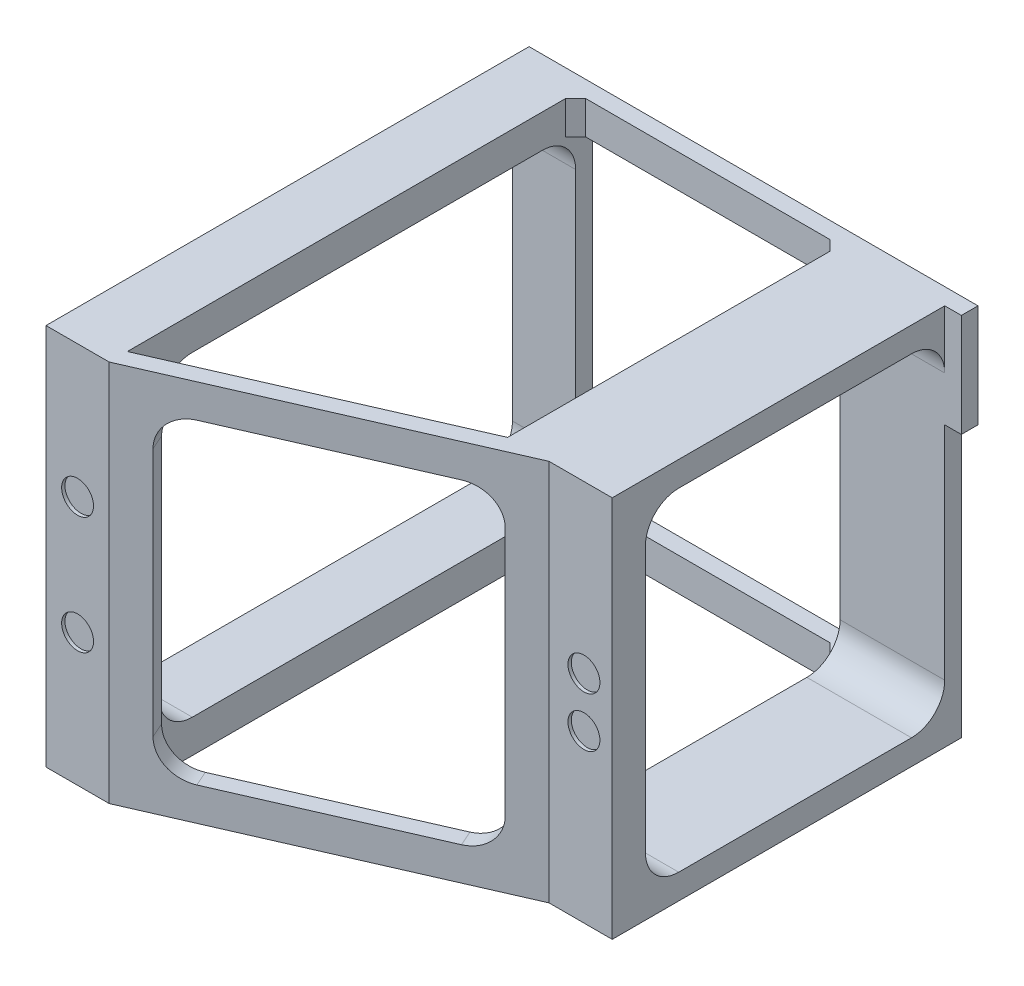
SolidWorks part; units mm, degrees
ref_plane "Front Plane" through (0, 0, 0) normal (1, 0, 0) x (0, 1, 0)
ref_plane "Top Plane" through (0, 0, 0) normal (0, 0, 1) x (0, 1, 0)
ref_plane "Right Plane" through (0, 0, 0) normal (0, 1, 0) x (-1, 0, 0)
sketch "Sketch2" plane through (0, 0, 0) normal (0, 0, 1) x (0, 1, 0)
  line L0 (0, 100.3268) -> (0, -104.3828) construction
  line L1 (0, 0) -> (145.436, 0) construction
  line L2 (-57.5, -65) -> (57.5, -65)
  line L3 (-57.5, -65) -> (-57.5, 65)
  line L4 (-57.5, 65) -> (57.5, 65)
  line L5 (57.5, -65) -> (57.5, 65)
  circle A0 centre (-18.09, -55.5) radius 4.8
  circle A1 centre (18.08, -55.5) radius 4.8
  dimension "D3" = 9.6
  dimension "D4" = 9.6
  dimension "D5" = 39.42
  dimension "D1" = 115
  dimension "D2" = 130
  dimension "D6" = 9.5
  dimension "D7" = 36.17
extrude "Boss-Extrude1" add sketch "Sketch2" along normal blind 5
sketch "Sketch3" plane through (0, 57.5, 0) normal (0, 1, 0) x (-1, 0, 0)
  line L0 (-65, 5) -> (-46, 5)
  line L1 (-65, 5) -> (65, 5) construction
  line L2 (-46, 5) -> (46, 45.27)
  line L3 (46, 45.27) -> (65, 45.27)
  line L4 (65, 45.27) -> (65, 39.812)
  line L6 (46, 39.812) -> (-33.5307, 5)
  line L7 (65, 5) -> (65, 0) construction
  line L8 (46, 39.812) -> (65, 39.812)
  line L9 (-65, 5) -> (-65, 0)
  line L10 (-65, 5) -> (-65, 0) construction
  line L11 (-65, 0) -> (-33.5307, 0)
  line L12 (-65, 0) -> (65, 0) construction
  line L13 (-33.5307, 0) -> (-33.5307, 5)
  point P5 (-33.5307, 0)
  dimension "D1" = 19
  dimension "D2" = 19
  dimension "D3" = 40.27
  dimension "D4" = 5
extrude "Boss-Extrude2" add sketch "Sketch3" against normal up to surface (115 mm away) up to face at (0, -57.5, 2.5)
sketch "Sketch4" plane through (0, 0, 5) normal (0, 0, 1) x (1, 0, 0)
  line L0 (33.5307, -57.5) -> (33.5307, 57.5)
  line L1 (-46, 57.5) -> (46, 57.5) construction
  line L2 (33.5307, 57.5) -> (-65, 57.5)
  line L3 (-65, 57.5) -> (-65, -57.5)
  line L4 (-65, -57.5) -> (33.5307, -57.5)
extrude "Cut-Extrude1" cut sketch "Sketch4" against normal blind 5
sketch "Sketch5" plane through (0, 0, 5) normal (0, 0, 1) x (1, 0, 0)
  line L0 (0, 0) -> (99.3947, 0) construction
  line L1 (65, -57.5) -> (65, 57.5) construction
  circle A0 centre (56.5, 7.5) radius 4.8
  circle A1 centre (56.5, -7.5) radius 4.8
  dimension "D2" = 9.6
  dimension "D3" = 9.6
  dimension "D1" = 15
  dimension "D4" = 7.5
  dimension "D5" = 8.5
extrude "Cut-Extrude2" cut sketch "Sketch5" against normal blind 1
sketch "Sketch6" plane through (0, 0, 45.27) normal (0, 0, 1) x (1, 0, 0)
  line L0 (0, 0) -> (90.3346, 0) construction
  line L1 (-65, -57.5) -> (-65, 57.5) construction
  circle A0 centre (-55.5, 17.65) radius 4.8
  circle A1 centre (-55.5, -17.65) radius 4.8
  dimension "D3" = 9.6
  dimension "D4" = 9.6
  dimension "D1" = 35.3
  dimension "D5" = 9.5
extrude "Cut-Extrude4" cut sketch "Sketch6" against normal blind 1
sketch "Sketch7" plane through (0, 0, 39.812) normal (0, 0, -1) x (1, 0, 0)
  line L1 (-65, -57.5) -> (-46, -57.5)
  line L2 (-65, -57.5) -> (-65, 57.5)
  line L3 (-65, 57.5) -> (-46, 57.5)
  line L4 (-46, -57.5) -> (-46, 57.5)
extrude "Boss-Extrude3" add sketch "Sketch7" along normal up to surface (39.812 mm away) up to face at (49.2654, 0, 0)
sketch "Sketch8" plane through (0, 0, 0) normal (0, 0, -1) x (1, 0, 0)
  line L1 (-65, 57.5) -> (-46, 57.5)
  line L2 (-65, 57.5) -> (-65, -57.5)
  line L3 (-65, -57.5) -> (-46, -57.5)
  line L4 (-46, 57.5) -> (-46, -57.5)
  line L5 (33.5307, 57.5) -> (65, 57.5)
  line L6 (33.5307, 57.5) -> (33.5307, -57.5)
  line L7 (33.5307, -57.5) -> (65, -57.5)
  line L8 (65, 57.5) -> (65, -57.5)
extrude "Boss-Extrude4" add sketch "Sketch8" along normal blind 100
sketch "Sketch9" plane through (-65, 0, 0) normal (-1, 0, 0) x (0, -1, 0)
  line L0 (57.5, 45.27) -> (-57.5, 45.27) construction
  line L1 (-37.5, -95) -> (37.5, -95)
  line L2 (-47.5, -85) -> (-47.5, 20.27)
  line L3 (-37.5, 30.27) -> (37.5, 30.27)
  line L4 (47.5, -85) -> (47.5, 20.27)
  line L5 (57.5, -100) -> (-57.5, -100) construction
  line L6 (-57.5, -100) -> (-57.5, 45.27) construction
  line L7 (57.5, 45.27) -> (57.5, -100) construction
  arc A0 (37.5, -95) -> (47.5, -85) centre (37.5, -85) ccw
  arc A1 (-37.5, -95) -> (-47.5, -85) centre (-37.5, -85) cw
  arc A2 (37.5, 30.27) -> (47.5, 20.27) centre (37.5, 20.27) cw
  arc A3 (-47.5, 20.27) -> (-37.5, 30.27) centre (-37.5, 20.27) cw
  dimension "D5" = 10
  dimension "D1" = 15
  dimension "D2" = 5
  dimension "D3" = 10
  dimension "D4" = 10
extrude "Cut-Extrude5" cut sketch "Sketch9" against normal up to surface (19 mm away) up to face at (-46, 0, -30.094)
sketch "Sketch10" plane through (65, 0, 0) normal (1, 0, 0) x (0, 1, 0)
  line L0 (-57.5, 5) -> (57.5, 5) construction
  line L1 (-40, -95) -> (40, -95)
  line L2 (-50, -85) -> (-50, -15)
  line L3 (-40, -5) -> (40, -5)
  line L4 (50, -85) -> (50, -15)
  line L5 (-57.5, 5) -> (-57.5, -100) construction
  line L6 (57.5, 5) -> (57.5, -100) construction
  line L7 (57.5, -100) -> (-57.5, -100) construction
  arc A0 (40, -95) -> (50, -85) centre (40, -85) ccw
  arc A1 (40, -5) -> (50, -15) centre (40, -15) cw
  arc A2 (-40, -95) -> (-50, -85) centre (-40, -85) cw
  arc A3 (-50, -15) -> (-40, -5) centre (-40, -15) cw
  dimension "D5" = 10
  dimension "D1" = 10
  dimension "D2" = 7.5
  dimension "D3" = 7.5
  dimension "D4" = 5
extrude "Cut-Extrude6" cut sketch "Sketch10" against normal up to surface (31.4693 mm away) up to face at (33.5307, 0, -47.5)
sketch "Sketch11" plane through (9.233, 0, 21.0935) normal (0.401, 0, 0.9161) x (0.9161, 0, -0.401)
  line L0 (-60.2925, 57.5) -> (40.1349, 57.5) construction
  line L1 (-40.2925, 47.5) -> (20.1349, 47.5)
  line L2 (-50.2925, 37.5) -> (-50.2925, -37.5)
  line L3 (-40.2925, -47.5) -> (20.1349, -47.5)
  line L4 (30.1349, 37.5) -> (30.1349, -37.5)
  line L5 (40.1349, -57.5) -> (-60.2925, -57.5) construction
  line L6 (40.1349, -57.5) -> (40.1349, 57.5) construction
  line L7 (-60.2925, -57.5) -> (-60.2925, 57.5) construction
  arc A0 (20.1349, -47.5) -> (30.1349, -37.5) centre (20.1349, -37.5) ccw
  arc A1 (-50.2925, -37.5) -> (-40.2925, -47.5) centre (-40.2925, -37.5) ccw
  arc A2 (20.1349, 47.5) -> (30.1349, 37.5) centre (20.1349, 37.5) cw
  arc A3 (-40.2925, 47.5) -> (-50.2925, 37.5) centre (-40.2925, 37.5) ccw
  dimension "D5" = 10
  dimension "D1" = 10
  dimension "D2" = 10
  dimension "D3" = 10
  dimension "D4" = 10
extrude "Cut-Extrude7" cut sketch "Sketch11" against normal up to surface (5 mm away) up to face at (-6.2346, 0, 22.406)
sketch "Sketch12" plane through (-65, 0, 0) normal (-1, 0, 0) x (0, 0, 1)
  line L0 (-95, 37.5) -> (-95, -37.5) construction
  line L1 (-100, 57.5) -> (-95, 57.5)
  line L2 (-100, 57.5) -> (-100, 47.5)
  line L3 (-100, 47.5) -> (-95, 47.5)
  line L4 (-95, 57.5) -> (-95, 47.5)
  line L5 (20.27, 47.5) -> (-85, 47.5) construction
  line L6 (-85, -47.5) -> (20.27, -47.5) construction
  line L7 (-100, -57.5) -> (-95, -57.5)
  line L8 (-100, -57.5) -> (-100, -47.5)
  line L9 (-100, -47.5) -> (-95, -47.5)
  line L10 (-95, -57.5) -> (-95, -47.5)
extrude "Boss-Extrude5" add sketch "Sketch12" against normal blind 100
chamfer "Chamfer1" distance 3 angle 45 4 edges at (-46, 52.5, -95) (33.5307, 52.5, -95) (33.5307, -52.5, -95) (-46, -52.5, -95)
sketch "Sketch13" plane through (65, 0, 0) normal (1, 0, 0) x (0, 0, -1)
  line L0 (95, 26.5) -> (95, 57.5)
  line L1 (95, -40) -> (95, 40) construction
  line L2 (95, 57.5) -> (100, 57.5)
  line L3 (100, 57.5) -> (100, 26.5)
  line L4 (100, 57.5) -> (100, -57.5) construction
  line L5 (100, 26.5) -> (95, 26.5)
  dimension "D1" = 31
extrude "Boss-Extrude6" add sketch "Sketch13" along normal blind 5
